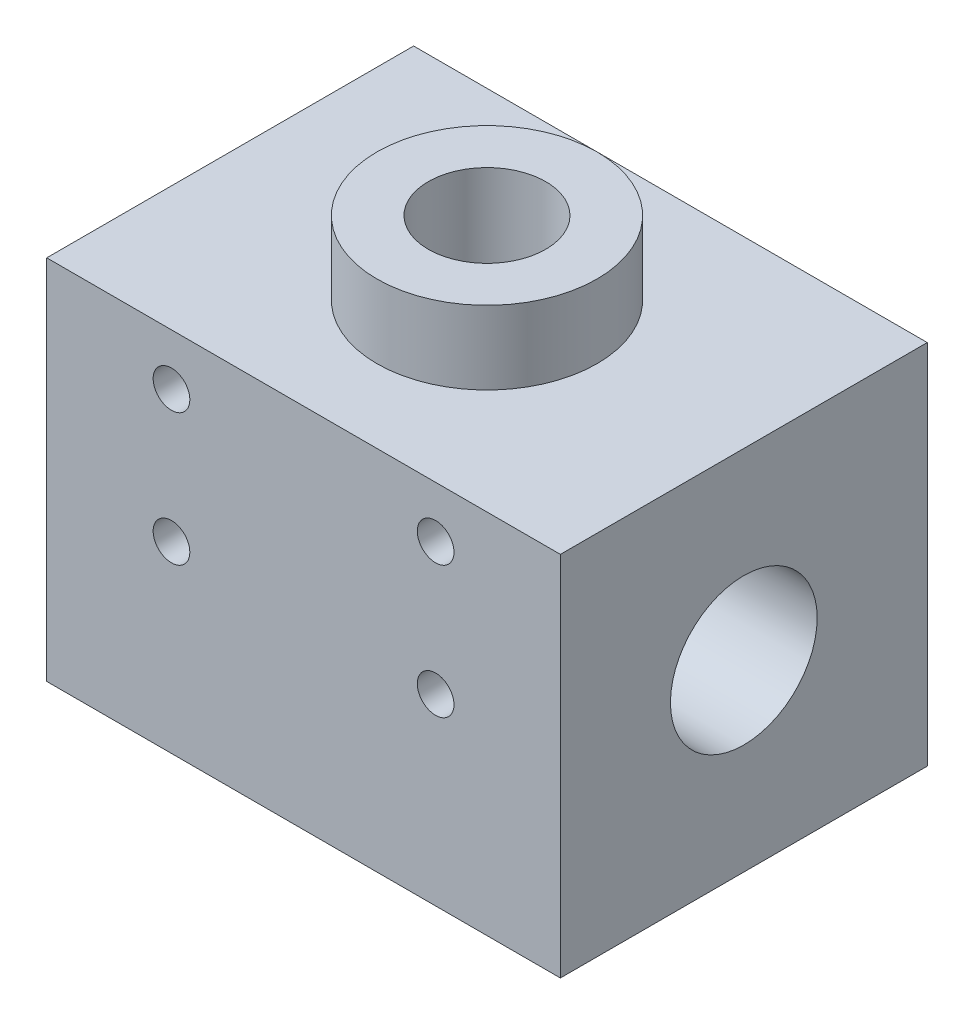
SolidWorks part; units mm, degrees
ref_plane "前视基准面" through (0, 0, 0) normal (0, 0, 1) x (1, 0, 0)
ref_plane "上视基准面" through (0, 0, 0) normal (0, 1, 0) x (1, 0, 0)
ref_plane "右视基准面" through (0, 0, 0) normal (1, 0, 0) x (0, 0, -1)
sketch "草图1" plane through (0, 0, 0) normal (0, 1, 0) x (1, 0, 0)
  line L0 (-35, 25) -> (35, 25)
  line L1 (35, 25) -> (35, -25)
  line L2 (35, -25) -> (-35, -25)
  line L3 (-35, -25) -> (-35, 25)
extrude "凸台-拉伸1" add sketch "草图1" along normal blind 50
ref_plane "基准面1" through (0, 50, 0) normal (0, 1, 0) x (1, 0, 0)
sketch "草图2" plane through (0, 50, 0) normal (0, 1, 0) x (1, 0, 0)
  circle A0 centre (0, 0) radius 15
extrude "凸台-拉伸2" add sketch "草图2" along normal blind 10
sketch "草图3" plane through (0, 0, 0) normal (1, 0, 0) x (0, 0, -1)
  circle A0 centre (0, 25) radius 10
extrude "切除-拉伸1" cut sketch "草图3" against normal mid plane 142
ref_plane "基准面2" through (0, 60, 0) normal (0, 1, 0) x (1, 0, 0)
sketch "草图4" plane through (0, 60, 0) normal (0, 1, 0) x (1, 0, 0)
  circle A0 centre (0, 0) radius 8
extrude "切除-拉伸2" cut sketch "草图4" against normal blind 35
ref_plane "基准面3" through (0, 0, 25) normal (0, 0, 1) x (1, 0, 0)
sketch "草图5" plane through (0, 0, 25) normal (0, 0, 1) x (1, 0, 0)
  circle A0 centre (-18, 25) radius 2.5
  circle A1 centre (18, 25) radius 2.5
  circle A2 centre (-18, 43) radius 2.5
  circle A3 centre (18, 43) radius 2.5
extrude "切除-拉伸3" cut sketch "草图5" against normal blind 10
